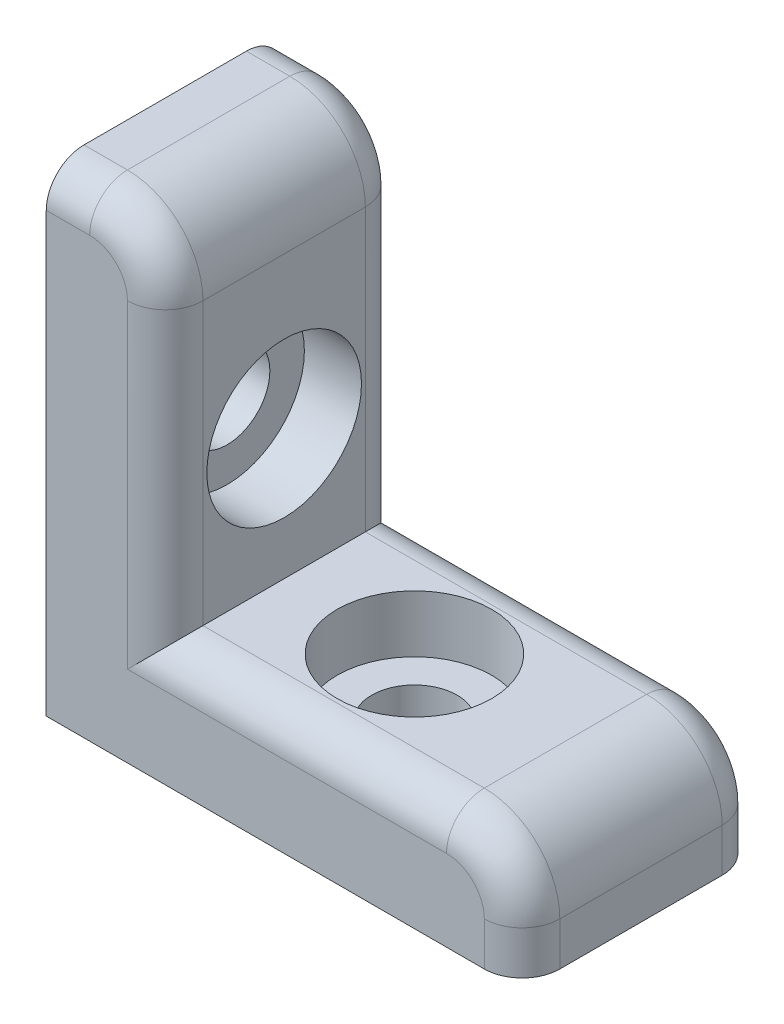
SolidWorks part; units mm, degrees
ref_plane "Front Plane" through (0, 0, 0) normal (0, 0, 1) x (1, 0, 0)
ref_plane "Top Plane" through (0, 0, 0) normal (0, 1, 0) x (1, 0, 0)
ref_plane "Right Plane" through (0, 0, 0) normal (1, 0, 0) x (0, 0, -1)
sketch "Sketch1" plane through (0, 0, 0) normal (0, 0, 1) x (1, 0, 0)
  line L0 (0, 0) -> (20, 0)
  line L2 (0, 20) -> (0, 0)
  line L3 (0, 20) -> (5, 20)
  line L4 (5, 20) -> (5, 5)
  line L5 (5, 5) -> (20, 5)
  line L6 (20, 5) -> (20, 0)
  dimension "D1" = 20
  dimension "D2" = 5
extrude "Boss-Extrude1" add sketch "Sketch1" along normal mid plane 10
sketch "Sketch2" plane through (5, 0, 0) normal (1, 0, 0) x (0, 0, -1)
  line L0 (0, 20) -> (0, 10.475) construction
  line L1 (-5, 20) -> (5, 20) construction
  point P1 (0, 10.475)
  dimension "D1" = 9.525
hole_wizard "CBORE for M3 Hex Socket Thin Head Cap Screw1" positions "Sketch2" profile "Sketch3" counterbore size "M3" standard "DIN" end condition through all
sketch "Sketch3" plane through (5, 10.475, 0) normal (0, 1, 0) x (0, 0, -1)
  line L0 (0, 0) -> (0, 5)
  line L1 (0, 5) -> (1.8, 5)
  line L3 (1.8, 5) -> (1.8, 2.4)
  line L4 (1.8, 2.4) -> (3.25, 2.4)
  line L5 (3.25, 2.4) -> (3.25, 0)
  line L7 (3.25, 0) -> (0, 0)
  line L11 (0, -6.35) -> (0, 107.95) construction
  dimension "Thru Hole Dia." = 3.6
  dimension "Thru Hole Depth" = 5
  dimension "C'Bore Dia." = 6.5
  dimension "C'Bore Depth" = 2.4
sketch "Sketch4" plane through (0, 5, 0) normal (0, 1, 0) x (1, 0, 0)
  line L0 (20, 0) -> (10.475, 0) construction
  line L1 (20, -5) -> (20, 5) construction
  point P1 (10.475, 0)
  dimension "D1" = 9.525
hole_wizard "CBORE for M3 Hex Socket Thin Head Cap Screw2" positions "Sketch4" profile "Sketch5" counterbore size "M3" standard "DIN" end condition through all
sketch "Sketch5" plane through (10.475, 5, 0) normal (1, 0, 0) x (0, 0, 1)
  line L0 (0, 0) -> (0, 5)
  line L1 (0, 5) -> (1.8, 5)
  line L3 (1.8, 5) -> (1.8, 2.4)
  line L4 (1.8, 2.4) -> (3.25, 2.4)
  line L5 (3.25, 2.4) -> (3.25, 0)
  line L7 (3.25, 0) -> (0, 0)
  line L11 (0, -6.35) -> (0, 107.95) construction
  dimension "Thru Hole Dia." = 3.6
  dimension "Thru Hole Depth" = 5
  dimension "C'Bore Dia." = 6.5
  dimension "C'Bore Depth" = 2.4
fillet "Fillet1" radius 3.175 2 edges at (20, 5, 0) (5, 20, 0)
fillet "Fillet2" radius 1.5875 12 edges at (10.9125, 5, -5) (20, 0.9125, -5) (0.9125, 20, -5) (5, 10.9125, -5) (20, 0.9125, 5) (10.9125, 5, 5) (5, 10.9125, 5) (0.9125, 20, 5) (19.0701, 4.0701, -5) (4.0701, 19.0701, -5) (19.0701, 4.0701, 5) (4.0701, 19.0701, 5)
